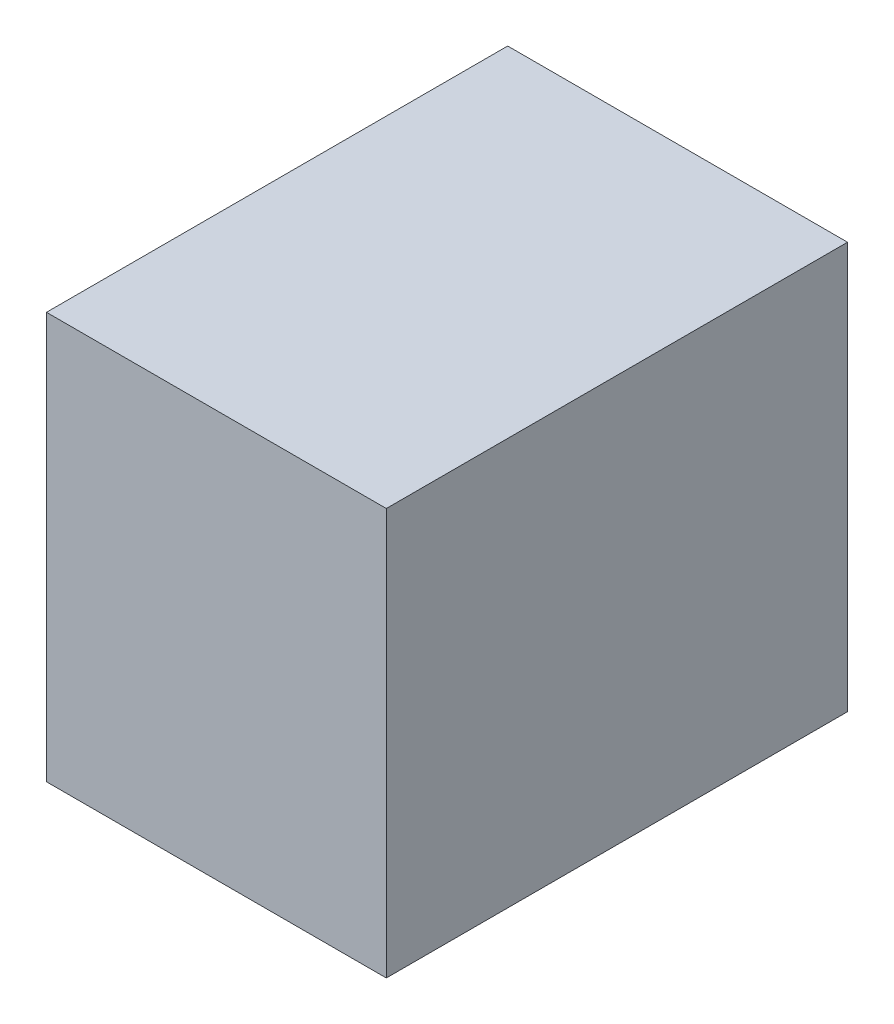
SolidWorks part; units mm, degrees
ref_plane "前视基准面" through (0, 0, 0) normal (0, 0, 1) x (1, 0, 0)
ref_plane "上视基准面" through (0, 0, 0) normal (0, 1, 0) x (1, 0, 0)
ref_plane "右视基准面" through (0, 0, 0) normal (1, 0, 0) x (0, 0, -1)
other "Configuration Table"
sketch "草图1" plane through (0, 0, 0) normal (0, 1, 0) x (1, 0, 0)
  line L1 (0, 0) -> (56, 0)
  line L2 (0, 0) -> (0, -76)
  line L3 (0, -76) -> (56, -76)
  line L4 (56, 0) -> (56, -76)
  dimension "D1" = 56
  dimension "D2" = 76
extrude "凸台-拉伸1" add sketch "草图1" along normal blind 67
